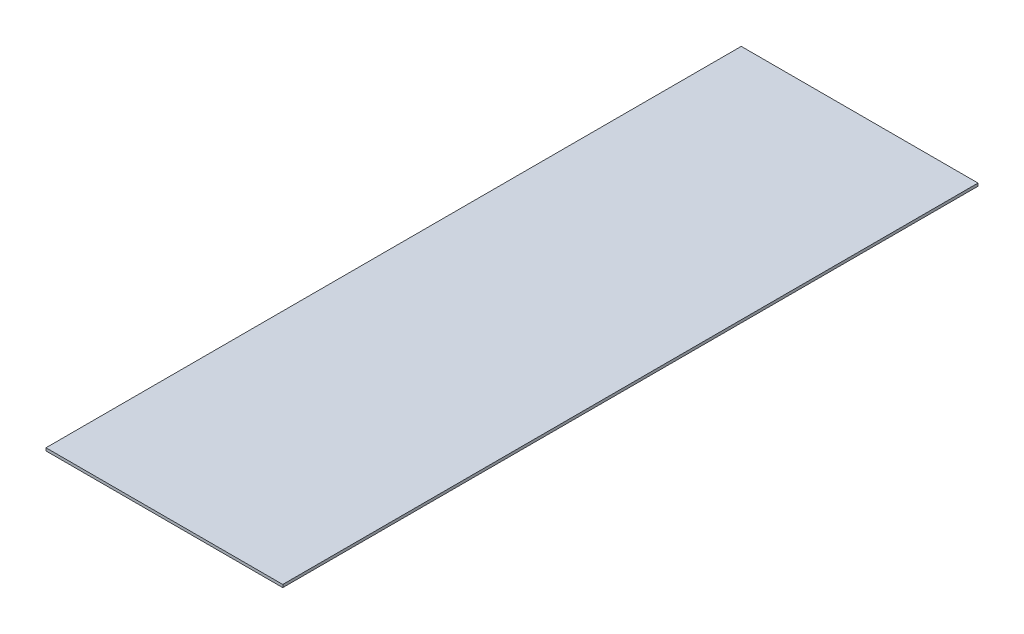
SolidWorks part; units mm, degrees
ref_plane "Front Plane" through (0, 0, 0) normal (0, 0, 1) x (1, 0, 0)
ref_plane "Top Plane" through (0, 0, 0) normal (0, 1, 0) x (1, 0, 0)
ref_plane "Right Plane" through (0, 0, 0) normal (1, 0, 0) x (0, 0, -1)
sketch "Sketch1" plane through (0, 0, 0) normal (0, 1, 0) x (1, 0, 0)
  line L0 (-170.27, 0) -> (-170.27, -500)
  line L1 (-170.27, -500) -> (0, -500)
  line L2 (0, -500) -> (0, 0)
  line L3 (0, 0) -> (-170.27, 0)
  dimension "D1" = 170.27
  dimension "D2" = 500
extrude "Boss-Extrude1" add sketch "Sketch1" along normal blind 2
equation "\"clip_tube_diam\"= 6mm"
equation "\"middle_tube_len\"= 500mm"
equation "\"horizontal_pipe_spacing\"= 260mm"
equation "\"belly_plate_width\" = 176mm"
equation "\"belly_bottom_width\" = 170.267mm"
equation "\"belly_length\"  = 500mm"
